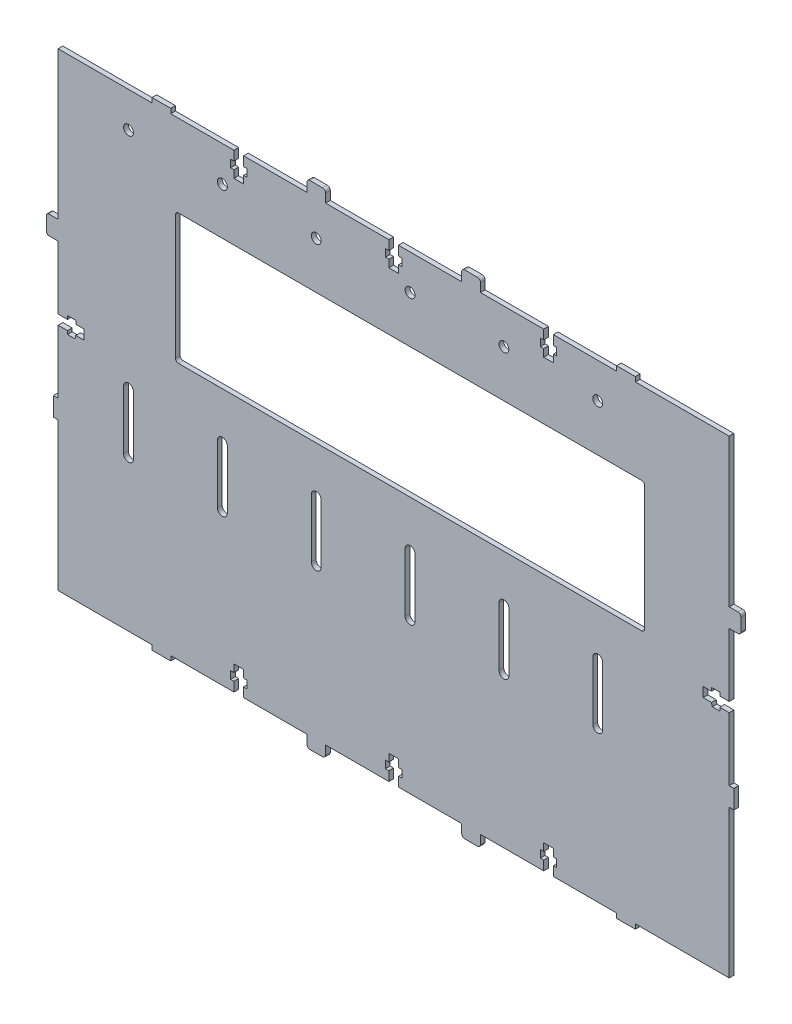
SolidWorks part; units mm, degrees
ref_plane "前视基准面" through (0, 0, 0) normal (0, 0, 1) x (1, 0, 0)
ref_plane "上视基准面" through (0, 0, 0) normal (0, 1, 0) x (1, 0, 0)
ref_plane "右视基准面" through (0, 0, 0) normal (1, 0, 0) x (0, 0, -1)
sketch "草图1" plane through (0, 0, 0) normal (0, 0, 1) x (1, 0, 0)
  line L0 (0, 0) -> (0, -4)
  line L1 (0, -4) -> (-1.45, -4)
  line L2 (-1.45, -4) -> (-1.45, -7.2)
  line L3 (-1.45, -7.2) -> (0, -7.2)
  line L4 (0, -7.2) -> (0, -10.4)
  line L5 (0, -10.4) -> (4.1, -10.4)
  line L6 (4.1, -10.4) -> (4.1, -7.2)
  line L7 (4.1, -7.2) -> (5.55, -7.2)
  line L8 (5.55, -7.2) -> (5.55, -4)
  line L9 (5.55, -4) -> (4.1, -4)
  line L10 (4.1, -4) -> (4.1, 0)
  line L11 (0, 0) -> (-26.95, 0)
  line L12 (-26.95, 0) -> (-26.95, 5)
  line L13 (-26.95, 5) -> (-34.95, 5)
  line L14 (-34.95, 5) -> (-34.95, 0)
  line L15 (2.05, -10.4) -> (2.05, -6.664) construction
  line L16 (-30.95, 5) -> (-30.95, -50.064) construction
  line L17 (-67.45, -4) -> (-66, -4)
  line L18 (-66, -7.2) -> (-67.45, -7.2)
  line L19 (-60.45, -7.2) -> (-61.9, -7.2)
  line L20 (-61.9, -4) -> (-60.45, -4)
  line L21 (-66, -4) -> (-66, 0)
  line L22 (-66, -10.4) -> (-66, -7.2)
  line L23 (-61.9, -10.4) -> (-66, -10.4)
  line L24 (-61.9, -7.2) -> (-61.9, -10.4)
  line L25 (-67.45, -7.2) -> (-67.45, -4)
  line L26 (-60.45, -4) -> (-60.45, -7.2)
  line L27 (-61.9, 0) -> (-61.9, -4)
  line L28 (-61.9, 0) -> (-34.95, 0)
  line L29 (31.05, 5) -> (39.05, 5)
  line L30 (31.05, 0) -> (31.05, 5)
  line L31 (39.05, 5) -> (39.05, 0)
  line L32 (4.1, 0) -> (31.05, 0)
  line L33 (66, 0) -> (39.05, 0)
  line L34 (66, 0) -> (66, -4)
  line L35 (64.55, -4) -> (64.55, -7.2)
  line L36 (71.55, -7.2) -> (71.55, -4)
  line L37 (66, -7.2) -> (66, -10.4)
  line L38 (66, -10.4) -> (70.1, -10.4)
  line L39 (70.1, -10.4) -> (70.1, -7.2)
  line L40 (70.1, -4) -> (70.1, 0)
  line L41 (66, -4) -> (64.55, -4)
  line L42 (64.55, -7.2) -> (66, -7.2)
  line L43 (70.1, -7.2) -> (71.55, -7.2)
  line L44 (71.55, -4) -> (70.1, -4)
  line L45 (68.05, -10.4) -> (68.05, -6.536) construction
  line L46 (70.1, 0) -> (97.05, 0)
  line L47 (132, 0) -> (105.05, 0)
  line L48 (97.05, 5) -> (97.05, 0)
  line L49 (105.05, 0) -> (105.05, 5)
  line L50 (105.05, 5) -> (97.05, 5)
  line L51 (-63.95, -10.4) -> (-63.95, -6.536) construction
  line L52 (-96.95, 5) -> (-96.95, -50.064) construction
  line L53 (-66, 0) -> (-92.95, 0)
  line L54 (-92.95, 5) -> (-92.95, 0)
  line L55 (-100.95, 5) -> (-92.95, 5)
  line L56 (-100.95, 0) -> (-100.95, 5)
  line L57 (-127.9, 0) -> (-100.95, 0)
  line L58 (2.05, -10.4) -> (-140.5, -10.4) construction
  line L59 (-127.9, 0) -> (-140.95, 0)
  line L60 (132, 0) -> (145.05, 0)
  line L63 (145.05, -200) -> (145.05, 0) construction
  line L64 (145.05, -100) -> (115.1583, -100) construction
  line L65 (-127.9, -200) -> (-140.95, -200)
  line L66 (2.05, -189.6) -> (2.05, -193.336) construction
  line L67 (4.1, -196) -> (4.1, -200)
  line L68 (5.55, -196) -> (4.1, -196)
  line L69 (5.55, -192.8) -> (5.55, -196)
  line L70 (4.1, -192.8) -> (5.55, -192.8)
  line L71 (4.1, -189.6) -> (4.1, -192.8)
  line L72 (0, -189.6) -> (4.1, -189.6)
  line L73 (0, -192.8) -> (0, -189.6)
  line L74 (-1.45, -192.8) -> (0, -192.8)
  line L75 (-1.45, -196) -> (-1.45, -192.8)
  line L76 (0, -196) -> (-1.45, -196)
  line L77 (0, -200) -> (0, -196)
  line L78 (132, -200) -> (145.05, -200)
  line L79 (68.05, -189.6) -> (68.05, -193.464) construction
  line L80 (105.05, -205) -> (97.05, -205)
  line L81 (105.05, -200) -> (105.05, -205)
  line L82 (97.05, -205) -> (97.05, -200)
  line L83 (132, -200) -> (105.05, -200)
  line L84 (70.1, -200) -> (97.05, -200)
  line L85 (71.55, -196) -> (70.1, -196)
  line L86 (70.1, -192.8) -> (71.55, -192.8)
  line L87 (64.55, -192.8) -> (66, -192.8)
  line L88 (66, -196) -> (64.55, -196)
  line L89 (70.1, -196) -> (70.1, -200)
  line L90 (70.1, -189.6) -> (70.1, -192.8)
  line L91 (66, -189.6) -> (70.1, -189.6)
  line L92 (66, -192.8) -> (66, -189.6)
  line L93 (71.55, -192.8) -> (71.55, -196)
  line L94 (64.55, -196) -> (64.55, -192.8)
  line L95 (66, -200) -> (66, -196)
  line L96 (66, -200) -> (39.05, -200)
  line L97 (4.1, -200) -> (31.05, -200)
  line L98 (39.05, -205) -> (39.05, -200)
  line L99 (31.05, -200) -> (31.05, -205)
  line L100 (31.05, -205) -> (39.05, -205)
  line L101 (2.05, -189.6) -> (-140.5, -189.6) construction
  line L102 (-96.95, -205) -> (-96.95, -149.936) construction
  line L103 (-63.95, -189.6) -> (-63.95, -193.464) construction
  line L104 (-30.95, -205) -> (-30.95, -149.936) construction
  line L105 (-127.9, -200) -> (-100.95, -200)
  line L106 (-100.95, -200) -> (-100.95, -205)
  line L107 (-100.95, -205) -> (-92.95, -205)
  line L108 (-92.95, -205) -> (-92.95, -200)
  line L109 (-66, -200) -> (-92.95, -200)
  line L110 (-61.9, -200) -> (-34.95, -200)
  line L111 (-61.9, -200) -> (-61.9, -196)
  line L112 (-60.45, -196) -> (-60.45, -192.8)
  line L113 (-67.45, -192.8) -> (-67.45, -196)
  line L114 (-61.9, -192.8) -> (-61.9, -189.6)
  line L115 (-61.9, -189.6) -> (-66, -189.6)
  line L116 (-66, -189.6) -> (-66, -192.8)
  line L117 (-66, -196) -> (-66, -200)
  line L118 (-61.9, -196) -> (-60.45, -196)
  line L119 (-60.45, -192.8) -> (-61.9, -192.8)
  line L120 (-66, -192.8) -> (-67.45, -192.8)
  line L121 (-67.45, -196) -> (-66, -196)
  line L122 (-34.95, -205) -> (-34.95, -200)
  line L123 (-26.95, -205) -> (-34.95, -205)
  line L124 (-26.95, -200) -> (-26.95, -205)
  line L125 (0, -200) -> (-26.95, -200)
  line L126 (145.05, -97.95) -> (141.05, -97.95)
  line L127 (141.05, -97.95) -> (141.05, -96.4903)
  line L128 (141.05, -96.4903) -> (137.5152, -96.4903)
  line L129 (137.5152, -96.4903) -> (137.5152, -97.95)
  line L130 (137.5152, -97.95) -> (133.9804, -97.95)
  line L131 (133.9804, -97.95) -> (133.9804, -102.05)
  line L132 (133.9804, -102.05) -> (137.5152, -102.05)
  line L133 (137.5152, -102.05) -> (137.8502, -103.4708)
  line L134 (137.8502, -103.4708) -> (141.05, -103.5097)
  line L135 (141.05, -103.5097) -> (141.05, -102.05)
  line L136 (141.05, -102.05) -> (145.05, -102.05)
  line L137 (133.9804, -100) -> (145.05, -100) construction
  line L138 (150.05, -67) -> (145.05, -67) construction
  line L139 (145.05, -71) -> (150.05, -71)
  line L140 (150.05, -71) -> (150.05, -63)
  line L141 (150.05, -63) -> (145.05, -63)
  line L142 (150.05, -133) -> (145.05, -133) construction
  line L143 (150.05, -137) -> (145.05, -137)
  line L144 (150.05, -129) -> (150.05, -137)
  line L145 (145.05, -129) -> (150.05, -129)
  line L146 (145.05, -97.95) -> (145.05, -71)
  line L147 (145.05, -102.05) -> (145.05, -129)
  line L148 (145.05, -137) -> (145.05, -200)
  line L149 (145.05, -63) -> (145.05, 0)
  line L150 (-145.95, -133) -> (-140.95, -133) construction
  line L151 (-145.95, -67) -> (-140.95, -67) construction
  line L152 (-140.95, -200) -> (145.05, 0) construction
  line L154 (-140.95, -102.05) -> (-140.95, -129)
  line L155 (-140.95, -97.95) -> (-140.95, -71)
  line L156 (-140.95, -129) -> (-145.95, -129)
  line L157 (-145.95, -129) -> (-145.95, -137)
  line L158 (-145.95, -137) -> (-140.95, -137)
  line L159 (-145.95, -63) -> (-140.95, -63)
  line L160 (-145.95, -71) -> (-145.95, -63)
  line L161 (-140.95, -71) -> (-145.95, -71)
  line L162 (-136.95, -102.05) -> (-140.95, -102.05)
  line L163 (-136.95, -103.5097) -> (-136.95, -102.05)
  line L164 (-133.7502, -103.4708) -> (-136.95, -103.5097)
  line L165 (-133.4152, -102.05) -> (-133.7502, -103.4708)
  line L166 (-129.8804, -102.05) -> (-133.4152, -102.05)
  line L167 (-129.8804, -97.95) -> (-129.8804, -102.05)
  line L168 (-133.4152, -97.95) -> (-129.8804, -97.95)
  line L169 (-133.4152, -96.4903) -> (-133.4152, -97.95)
  line L170 (-136.95, -96.4903) -> (-133.4152, -96.4903)
  line L171 (-136.95, -97.95) -> (-136.95, -96.4903)
  line L172 (-140.95, -97.95) -> (-136.95, -97.95)
  line L173 (-140.95, 0) -> (-140.95, -63)
  line L174 (-140.95, -200) -> (-140.95, -137)
  line L175 (-90.95, -35) -> (-90.95, -90.5)
  line L176 (-90.95, -90.5) -> (109.05, -90.5)
  line L177 (-110.95, -135.5) -> (-110.95, -110.5) construction
  line L178 (-113.05, -135.5) -> (-113.05, -110.5)
  line L179 (-108.85, -135.5) -> (-108.85, -110.5)
  line L180 (-70.95, -135.5) -> (-70.95, -110.5) construction
  line L181 (-73.05, -135.5) -> (-73.05, -110.5)
  line L182 (-68.85, -135.5) -> (-68.85, -110.5)
  line L183 (-30.95, -135.5) -> (-30.95, -110.5) construction
  line L184 (-33.05, -135.5) -> (-33.05, -110.5)
  line L185 (-28.85, -135.5) -> (-28.85, -110.5)
  line L186 (9.05, -135.5) -> (9.05, -110.5) construction
  line L187 (6.95, -135.5) -> (6.95, -110.5)
  line L188 (11.15, -135.5) -> (11.15, -110.5)
  line L189 (49.05, -135.5) -> (49.05, -110.5) construction
  line L190 (46.95, -135.5) -> (46.95, -110.5)
  line L191 (51.15, -135.5) -> (51.15, -110.5)
  line L192 (89.05, -135.5) -> (89.05, -110.5) construction
  line L193 (86.95, -135.5) -> (86.95, -110.5)
  line L194 (91.15, -135.5) -> (91.15, -110.5)
  line L195 (129.05, -135.5) -> (129.05, -110.5) construction
  line L196 (126.95, -135.5) -> (126.95, -110.5) construction
  line L197 (131.15, -135.5) -> (131.15, -110.5) construction
  line L198 (109.05, -35) -> (109.05, -90.5)
  line L199 (-110.95, -15) -> (129.05, -15) construction
  line L200 (-110.95, -15) -> (-110.95, -110.5) construction
  line L201 (-110.95, -110.5) -> (129.05, -110.5) construction
  line L202 (129.05, -15) -> (129.05, -110.5) construction
  line L203 (-90.95, -35) -> (109.05, -35)
  circle A1 centre (-110.95, -15) radius 2.1
  circle A2 centre (-70.95, -15) radius 2.1
  circle A3 centre (-30.95, -15) radius 2.1
  circle A4 centre (9.05, -15) radius 2.1
  circle A5 centre (49.05, -15) radius 2.1
  circle A6 centre (89.05, -15) radius 2.1
  circle A7 centre (129.05, -15) radius 2.1 construction
  arc A8 (-113.05, -135.5) -> (-108.85, -135.5) centre (-110.95, -135.5) ccw
  arc A9 (-108.85, -110.5) -> (-113.05, -110.5) centre (-110.95, -110.5) ccw
  arc A10 (-73.05, -135.5) -> (-68.85, -135.5) centre (-70.95, -135.5) ccw
  arc A11 (-68.85, -110.5) -> (-73.05, -110.5) centre (-70.95, -110.5) ccw
  arc A12 (-33.05, -135.5) -> (-28.85, -135.5) centre (-30.95, -135.5) ccw
  arc A13 (-28.85, -110.5) -> (-33.05, -110.5) centre (-30.95, -110.5) ccw
  arc A14 (6.95, -135.5) -> (11.15, -135.5) centre (9.05, -135.5) ccw
  arc A15 (11.15, -110.5) -> (6.95, -110.5) centre (9.05, -110.5) ccw
  arc A16 (46.95, -135.5) -> (51.15, -135.5) centre (49.05, -135.5) ccw
  arc A17 (51.15, -110.5) -> (46.95, -110.5) centre (49.05, -110.5) ccw
  arc A18 (86.95, -135.5) -> (91.15, -135.5) centre (89.05, -135.5) ccw
  arc A19 (91.15, -110.5) -> (86.95, -110.5) centre (89.05, -110.5) ccw
  arc A20 (126.95, -135.5) -> (131.15, -135.5) centre (129.05, -135.5) ccw construction
  arc A21 (131.15, -110.5) -> (126.95, -110.5) centre (129.05, -110.5) ccw construction
  point P166 (139.4501, -103.4903)
  point P210 (-110.95, -123)
  point P218 (-70.95, -123)
  point P225 (-30.95, -123)
  point P232 (9.05, -123)
  point P239 (49.05, -123)
  point P246 (89.05, -123)
  point P253 (129.05, -123)
  dimension "D19" = 40
  dimension "D21" = 40
  dimension "D22" = 40
  dimension "D23" = 40
  dimension "D24" = 40
  dimension "D25" = 40
  dimension "D27" = 7
  dimension "D28" = 15
  dimension "D1" = 4.1
  dimension "D2" = 33
  dimension "D3" = 4
  dimension "D4" = 3.2
  dimension "D5" = 7
  dimension "D6" = 200
  dimension "D7" = 5
  dimension "D8" = 286
  dimension "D9" = 4.1
  dimension "D10" = 4
  dimension "D11" = 3.2
  dimension "D12" = 7
  dimension "D13" = 8
  dimension "D14" = 5
  dimension "D16" = 33
  dimension "D17" = 8
  dimension "D20" = 30
  dimension "D26" = 108
  dimension "D29" = 20
extrude "凸台-拉伸1" add sketch "草图1" along normal blind 2 contours L33 L31 L29 L30 L32 L10 L9 L8 L7 L6 L5 L4 L3 L2 L1 L0 L11 L12 L13 L14 L28 L27 L20 L26 L19 L24 L23 L22 L18 L25 L17 L21 L53 L54 L55 L56 L57 L59 L173 L159 L160 L161 L155 L172 L171 L170 L169 L168 L167 L166 L165 L164 L163 L162 L154 L156 L157 L158 L174 L65 L105 L106 L107 L108 L109 L117 L121 L113 L120 L116 L115 L114 L119 L112 L118 L111 L110 L122 L123 L124 L125 L77 L76 L75 L74 L73 L72 L71 L70 L69 L68 L67 L97 L99 L100 L98 L96 L95 L88 L94 L87 L92 L91 L90 L86 L93 L85 L89 L84 L82 L80 L81 L83 L78 L148 L143 L144 L145 L147 L136 L135 L134 L133 L132 L131 L130 L129 L128 L127 L126 L146 L139 L140 L141 L149 L60 L47 L49 L50 L48 L46 L40 L44 L36 L43 L39 L38 L37 L42 L35 L41 L34
sketch "草图2" plane through (0, -200, 0) normal (0, -1, 0) x (1, 0, 0)
  line L0 (0, 1) -> (4.1, 1)
  line L1 (0, 2) -> (0, 0) construction
  line L2 (4.1, 2) -> (4.1, 0) construction
  circle A0 centre (2.05, 1) radius 2.05
sketch "草图3" plane through (0, 0, 0) normal (0, 1, 0) x (1, 0, 0)
  line L0 (0, -1) -> (4.1, -1)
  line L1 (0, -2) -> (0, 0) construction
  line L2 (4.1, -2) -> (4.1, 0) construction
  circle A0 centre (2.05, -1) radius 2.05
fillet "圆角1" radius 1 4 edges at (-145.95, -137, 1) (-145.95, -129, 1) (-145.95, -63, 1) (-145.95, -71, 1)
fillet "圆角2" radius 1.3 24 edges at (97.05, 5, 1) (105.05, 5, 1) (39.05, 5, 1) (31.05, 5, 1) (-26.95, 5, 1) (-34.95, 5, 1) (-100.95, 5, 1) (-92.95, 5, 1) (-100.95, -205, 1) (-92.95, -205, 1) (-34.95, -205, 1) (-26.95, -205, 1) (31.05, -205, 1) (39.05, -205, 1) (97.05, -205, 1) (105.05, -205, 1) (150.05, -137, 1) (150.05, -129, 1) (150.05, -63, 1) (150.05, -71, 1) (109.05, -90.5, 1) (109.05, -35, 1) (-90.95, -90.5, 1) (-90.95, -35, 1)
sketch "草图4" plane through (0, 0, 2) normal (0, 0, 1) x (1, 0, 0)
  line L0 (-66, 0) -> (-92.95, 0) construction
  line L1 (-103.3854, 10.2629) -> (-87.2942, 10.2629)
  line L2 (-103.3854, 10.2629) -> (-103.3854, 2)
  line L3 (-103.3854, 2) -> (-87.2942, 2)
  line L4 (-87.2942, 10.2629) -> (-87.2942, 2)
  line L5 (90.8931, 10.2629) -> (110.825, 10.2629)
  line L6 (90.8931, 10.2629) -> (90.8931, 2)
  line L7 (90.8931, 2) -> (110.825, 2)
  line L8 (110.825, 10.2629) -> (110.825, 2)
  line L9 (-104.6148, -202) -> (-90.1272, -202)
  line L10 (-104.6148, -202) -> (-104.6148, -207.89)
  line L11 (-104.6148, -207.89) -> (-90.1272, -207.89)
  line L12 (-90.1272, -202) -> (-90.1272, -207.89)
  line L13 (94.1099, -202) -> (110.825, -202)
  line L14 (94.1099, -202) -> (94.1099, -210.1778)
  line L15 (94.1099, -210.1778) -> (110.825, -210.1778)
  line L16 (110.825, -202) -> (110.825, -210.1778)
  line L17 (145.05, 0) -> (105.05, 0) construction
  line L18 (-66, -200) -> (-92.95, -200) construction
  line L19 (105.05, -200) -> (145.05, -200) construction
  line L20 (-140.95, 0) -> (-140.95, -63) construction
  line L21 (-153.0557, -111.648) -> (-142.95, -111.648)
  line L22 (-153.0557, -111.648) -> (-153.0557, -137.7144)
  line L23 (-153.0557, -137.7144) -> (-142.95, -137.7144)
  line L24 (-142.95, -111.648) -> (-142.95, -137.7144)
  line L25 (147.05, -113.9361) -> (152.7115, -113.9361)
  line L26 (147.05, -113.9361) -> (147.05, -141.3929)
  line L27 (147.05, -141.3929) -> (152.7115, -141.3929)
  line L28 (152.7115, -113.9361) -> (152.7115, -141.3929)
  line L29 (145.05, -63) -> (145.05, 0) construction
  dimension "D1" = 2
  dimension "D2" = 2
  dimension "D3" = 2
  dimension "D4" = 2
  dimension "D5" = 2
  dimension "D6" = 2
extrude "切除-拉伸1" cut sketch "草图4" against normal blind 2
